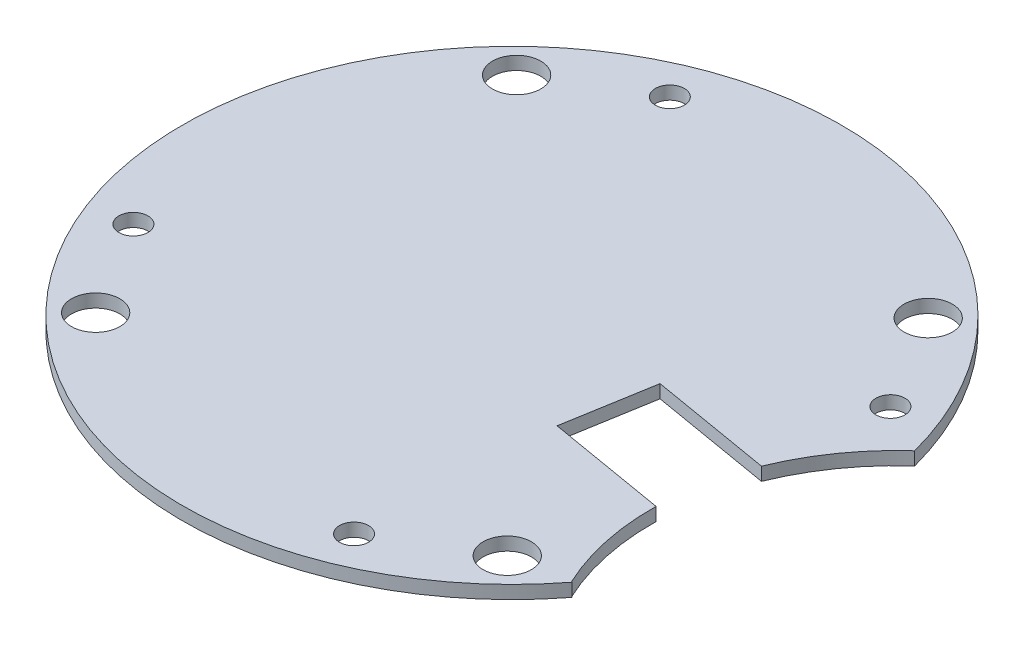
SolidWorks part; units mm, degrees
ref_plane "Alzado" through (0, 0, 0) normal (0, 0, 1) x (1, 0, 0)
ref_plane "Planta" through (0, 0, 0) normal (0, 1, 0) x (1, 0, 0)
ref_plane "Vista lateral" through (0, 0, 0) normal (1, 0, 0) x (0, 0, -1)
sketch "Sketch1" plane through (0, 0, 0) normal (0, 1, 0) x (1, 0, 0)
  circle A0 centre (0, 0) radius 37.5
  dimension "D1" = 75
extrude "Boss-Extrude1" add sketch "Sketch1" along normal blind 1.5
sketch "Sketch2" plane through (0, 1.5, 0) normal (0, 1, 0) x (1, 0, 0)
sketch "Sketch3" plane through (0, 1.5, 0) normal (0, 1, 0) x (1, 0, 0)
  line L0 (0, 0) -> (0, 17.0335) construction
  circle A0 centre (-7, 0) radius 2
  circle A1 centre (7, 0) radius 2
  dimension "D1" = 4
  dimension "D2" = 7
sketch "Sketch4" plane through (0, 0, 0) normal (0, -1, 0) x (1, 0, 0)
  circle A1 centre (0, 0) radius 7.25
extrude "Boss-Extrude2" add sketch "Sketch4" along normal blind 6
sketch "Sketch5" plane through (0, -6, 0) normal (0, -1, 0) x (1, 0, 0)
  circle A0 centre (0, 0) radius 5.5
  dimension "D1" = 11
extrude "Cut-Extrude2" cut sketch "Sketch5" against normal blind 7
sketch "Sketch6" plane through (0, 0, 0) normal (0, -1, 0) x (1, 0, 0)
  circle A1 centre (0, 0) radius 37.5
  circle A4 centre (0, 0) radius 37.5
  dimension "D1" = 0
sketch "Sketch7" plane through (0, 1.5, 0) normal (0, 1, 0) x (1, 0, 0)
sketch "Sketch8" plane through (0, 1.5, 0) normal (0, 1, 0) x (1, 0, 0)
  circle A0 centre (-23.4164, 23.9496) radius 2.75
  circle A1 centre (23.9496, 23.4164) radius 2.75
  circle A2 centre (23.4164, -23.9496) radius 2.75
  circle A3 centre (-23.9496, -23.4164) radius 2.75
  circle A4 centre (-30.5199, -12.5514) radius 1.65
  circle A5 centre (-12.5514, 30.5199) radius 1.65
  circle A6 centre (30.5199, 12.5514) radius 1.65
  circle A7 centre (12.5514, -30.5199) radius 1.65
  point P12 (0, 0)
  point P22 (0, 0)
  dimension "D1" = 5.5
  dimension "D2" = 4
  dimension "D3" = 3.3
  dimension "D4" = 4
extrude "Cut-Extrude3" cut sketch "Sketch8" against normal blind 10
sketch "Sketch9" plane through (0, 1.5, 0) normal (0, 1, 0) x (1, 0, 0)
  line L0 (15.1529, 1.7001) -> (13.4507, -8.3163) construction
  line L1 (29.0581, -0.663) -> (15.1529, 1.7001) construction
  line L2 (13.4507, -8.3163) -> (27.0237, -10.623) construction
  line L3 (15.1529, 1.7001) -> (13.4507, -8.3163)
  line L4 (29.0581, -0.663) -> (15.1529, 1.7001)
  line L5 (13.4507, -8.3163) -> (27.0237, -10.623)
  arc A0 (36.243, 9.5554) -> (29.0581, -0.663) centre (54.7623, -11.1012) ccw construction
  arc A1 (27.0237, -10.623) -> (29.6579, -22.9091) centre (54.7623, -11.1012) ccw construction
  arc A2 (36.243, 9.5554) -> (29.0581, -0.663) centre (54.7623, -11.1012) ccw
  arc A3 (27.0237, -10.623) -> (29.6579, -22.9091) centre (54.7623, -11.1012) ccw
  arc A4 (29.6579, -22.9091) -> (36.243, 9.5554) centre (23.0939, -4.6776) ccw
extrude "Cut-Extrude5" cut sketch "Sketch9" against normal mid plane 10
